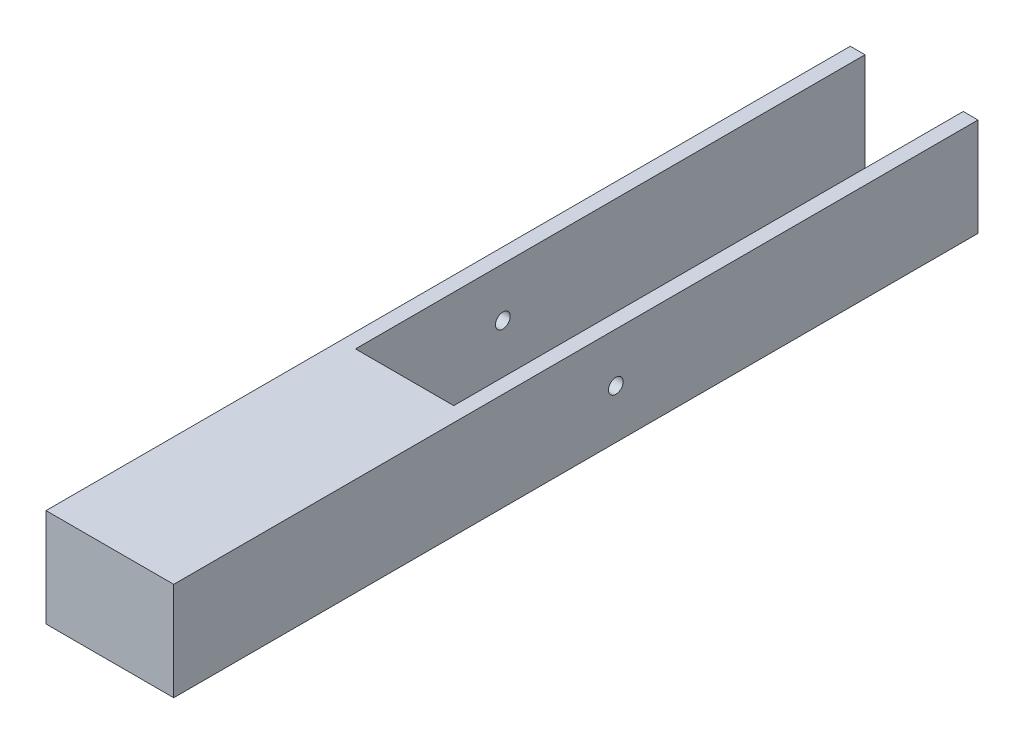
SolidWorks part; units mm, degrees
ref_plane "Front Plane" through (0, 0, 0) normal (0, 0, 1) x (1, 0, 0)
ref_plane "Top Plane" through (0, 0, 0) normal (0, 1, 0) x (1, 0, 0)
ref_plane "Right Plane" through (0, 0, 0) normal (1, 0, 0) x (0, 0, -1)
sketch "Sketch2" plane through (0, 0, 0) normal (0, 0, 1) x (1, 0, 0)
  line L1 (0, 0) -> (25.4, 0)
  line L2 (0, 0) -> (0, 25.4)
  line L3 (0, 25.4) -> (25.4, 25.4)
  line L4 (25.4, 0) -> (25.4, 25.4)
  dimension "D1" = 25.4
extrude "Boss-Extrude1" add sketch "Sketch2" along normal blind 76.2
sketch "Sketch3" plane through (25.4, 0, 0) normal (1, 0, 0) x (0, 0, -1)
  line L1 (-76.2, 0) -> (131.7248, 0)
  line L2 (-76.2, 0) -> (-76.2, 25.4)
  line L3 (-76.2, 25.4) -> (131.7248, 25.4)
  line L4 (131.7248, 0) -> (131.7248, 25.4)
  line L6 (-76.2, 25.4) -> (0, 25.4) construction
extrude "Boss-Extrude2" add sketch "Sketch3" along normal blind 3.81
sketch "Sketch4" plane through (0, 0, 0) normal (-1, 0, 0) x (0, 0, 1)
  line L0 (76.2, 0) -> (0, 0) construction
  line L1 (76.2, 0) -> (-131.7248, 0)
  line L2 (76.2, 0) -> (76.2, 25.4)
  line L3 (76.2, 25.4) -> (-131.7248, 25.4)
  line L4 (-131.7248, 0) -> (-131.7248, 25.4)
  line L5 (76.2, 25.4) -> (0, 25.4) construction
  line L6 (-131.7248, 0) -> (-131.7248, 25.4) construction
extrude "Boss-Extrude3" add sketch "Sketch4" along normal blind 3.81
sketch "Sketch5" plane through (-3.81, 0, 0) normal (-1, 0, 0) x (0, 0, 1)
  line L0 (-131.7248, 0) -> (76.2, 0) construction
  line L1 (76.2, 0) -> (76.2, 25.4) construction
  circle A0 centre (-38.1, 12.7) radius 1.905
  dimension "D2" = 3.81
  dimension "D1" = 12.7
  dimension "D3" = 114.3
extrude "Cut-Extrude1" cut sketch "Sketch5" against normal through all
